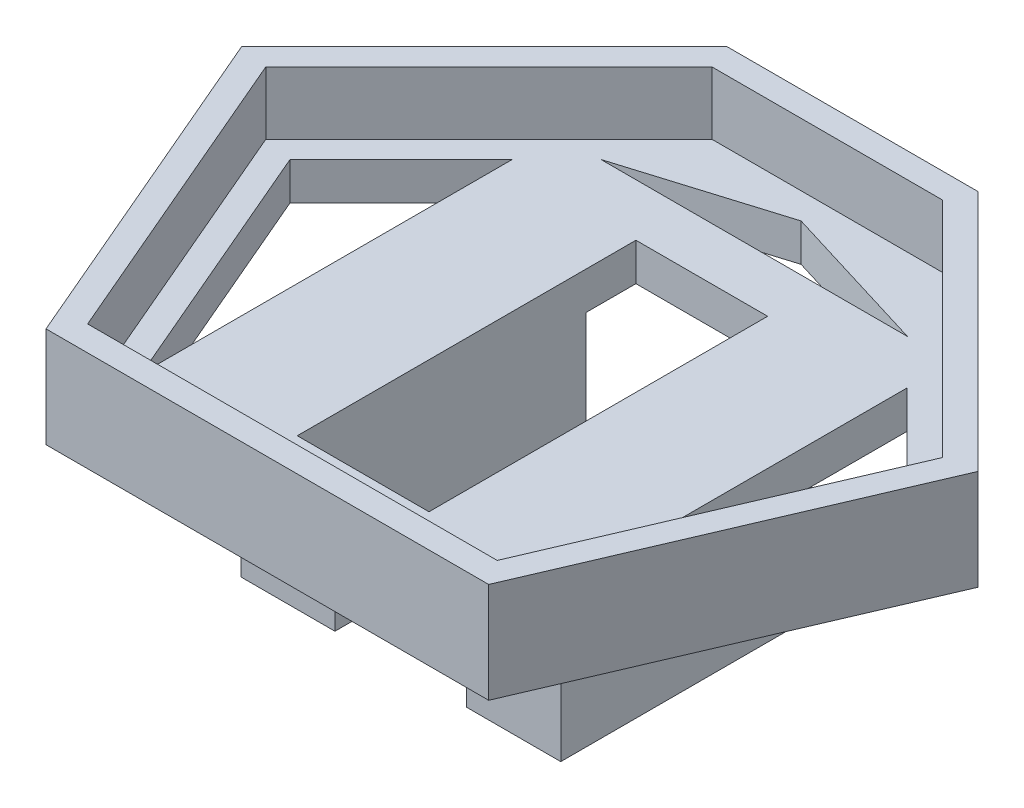
SolidWorks part; units mm, degrees
ref_plane "Front Plane" through (0, 0, 0) normal (0, 0, 1) x (1, 0, 0)
ref_plane "Top Plane" through (0, 0, 0) normal (0, 1, 0) x (1, 0, 0)
ref_plane "Right Plane" through (0, 0, 0) normal (1, 0, 0) x (0, 0, -1)
sketch "Sketch1" plane through (0, 0, 0) normal (0, 1, 0) x (1, 0, 0)
  line L2 (8.9892, 5.9961) -> (-8.9892, 5.9961) construction
  line L6 (-8.9892, 5.9961) -> (-26.3848, -11.3995) construction
  line L7 (-26.3848, -11.3995) -> (-16, -35.6421) construction
  line L8 (-16, -35.6421) -> (16, -35.6421) construction
  line L9 (16, -35.6421) -> (26.3848, -11.3995) construction
  line L11 (26.3848, -11.3995) -> (8.9892, 5.9961) construction
  line L12 (9.1963, 6.4961) -> (-9.1963, 6.4961)
  line L13 (-9.1963, 6.4961) -> (-26.9777, -11.2853)
  line L14 (-26.9777, -11.2853) -> (-16.3298, -36.1421)
  line L16 (-16.3298, -36.1421) -> (16.3298, -36.1421)
  line L17 (16.3298, -36.1421) -> (26.9777, -11.2853)
  line L18 (26.9777, -11.2853) -> (9.1963, 6.4961)
  line L19 (10.0247, 8.4961) -> (-10.0247, 8.4961)
  line L20 (-10.0247, 8.4961) -> (-29.3492, -10.8283)
  line L21 (-29.3492, -10.8283) -> (-17.6488, -38.1421)
  line L22 (-17.6488, -38.1421) -> (17.6488, -38.1421)
  line L23 (17.6488, -38.1421) -> (29.3492, -10.8283)
  line L24 (29.3492, -10.8283) -> (10.0247, 8.4961)
  dimension "D1" = 0.5
  dimension "D2" = 2
extrude "Boss-Extrude1" add sketch "Sketch1" along normal blind 5
sketch "Sketch2" plane through (0, 0, 0) normal (0, -1, 0) x (-1, 0, 0)
  line L0 (17.6488, -38.1421) -> (-17.6488, -38.1421)
  line L1 (-17.6488, -38.1421) -> (-29.3492, -10.8283)
  line L2 (-29.3492, -10.8283) -> (-10.0247, 8.4961)
  line L3 (-10.0247, 8.4961) -> (10.0247, 8.4961)
  line L4 (10.0247, 8.4961) -> (29.3492, -10.8283)
  line L5 (29.3492, -10.8283) -> (17.6488, -38.1421)
extrude "Boss-Extrude2" add sketch "Sketch2" along normal blind 3
sketch "Sketch3" plane through (0, -3, 0) normal (0, -1, 0) x (-1, 0, 0)
  line L0 (0, 8.4961) -> (0, -38.1421) construction
  line L1 (10.0247, 8.4961) -> (-10.0247, 8.4961) construction
  line L2 (-17.6488, -38.1421) -> (17.6488, -38.1421) construction
  line L3 (5.25, -7.5039) -> (12.7574, -7.5039)
  line L4 (5.25, -7.5039) -> (-5.25, -7.5039) construction
  line L5 (5.25, -7.5039) -> (5.25, -27.5039)
  line L6 (5.25, -27.5039) -> (-5.25, -27.5039) construction
  line L7 (-5.25, -7.5039) -> (-5.25, -27.5039)
  line L10 (12.7574, -7.5039) -> (12.7574, -27.5039)
  line L11 (12.7574, -27.5039) -> (5.25, -27.5039)
  line L12 (-12.7574, -27.5039) -> (-5.25, -27.5039)
  line L13 (-12.7574, -7.5039) -> (-12.7574, -27.5039)
  line L14 (-5.25, -7.5039) -> (-12.7574, -7.5039)
  dimension "D1" = 10.5
  dimension "D2" = 20
  dimension "D3" = 16
extrude "Boss-Extrude3" add sketch "Sketch3" along normal blind 12
sketch "Sketch5" plane through (0, 0, 7.5039) normal (0, 0, -1) x (-1, 0, 0)
  line L0 (0, -3) -> (0, -15.9929) construction
  line L1 (10.0247, -3) -> (-10.0247, -3) construction
  line L2 (-5.25, -15) -> (-5.25, -3) construction
  line L3 (-9.75, -13) -> (9.75, -13)
  line L4 (-9.75, -13) -> (-9.75, -10.85)
  line L5 (-9.75, -10.85) -> (9.75, -10.85)
  line L6 (9.75, -13) -> (9.75, -10.85)
  line L7 (-9.75, -13) -> (9.75, -10.85) construction
  line L8 (-9.75, -10.85) -> (9.75, -13) construction
  line L9 (-5.25, -15) -> (-12.7574, -15) construction
  point P5 (0, -11.925)
  dimension "D1" = 4.5
  dimension "D2" = 2
  dimension "D3" = 2.15
extrude "Cut-Extrude2" cut sketch "Sketch5" against normal blind 18
sketch "Sketch6" plane through (0, -3, 0) normal (0, -1, 0) x (-1, 0, 0)
  line L0 (0, 8.4961) -> (0, -38.1421) construction
  line L2 (5.25, -7.5039) -> (5.25, -30.5039)
  line L3 (5.25, -30.5039) -> (-5.25, -30.5039)
  line L4 (-5.25, -5.5039) -> (-5.25, -30.5039)
  line L5 (10.0247, 8.4961) -> (-10.0247, 8.4961) construction
  line L6 (-17.6488, -38.1421) -> (17.6488, -38.1421) construction
  line L7 (-10.0247, 8.4961) -> (-29.3492, -10.8283) construction
  line L8 (-29.3492, -10.8283) -> (-17.6488, -38.1421) construction
  line L11 (-24.6061, -11.7422) -> (-13.9719, -36.5671) construction
  line L12 (-24.6061, -11.7422) -> (-15.7574, -32.399)
  line L13 (-15.7574, -2.8934) -> (-15.7574, -32.399)
  line L14 (-12.7574, -7.5039) -> (-12.7574, -27.5039) construction
  line L15 (-12.2192, 0.677) -> (12.2192, 0.677)
  line L16 (-12.2192, 0.677) -> (0, 4.4128)
  line L17 (-15.7574, -2.8934) -> (-24.6061, -11.7422)
  line L18 (-7.1963, 5.6677) -> (-24.6061, -11.7422) construction
  line L19 (12.2192, 0.677) -> (0, 4.4128)
  line L20 (15.7574, -2.8934) -> (24.6061, -11.7422)
  line L21 (15.7574, -2.8934) -> (15.7574, -32.399)
  line L22 (24.6061, -11.7422) -> (15.7574, -32.399)
  line L23 (-5.25, -5.5039) -> (-5.25, -3.5039)
  line L24 (-5.25, -3.5039) -> (5.25, -3.5039)
  line L25 (5.25, -7.5039) -> (5.25, -3.5039)
  line L26 (-12.7574, -27.5039) -> (-5.25, -27.5039) construction
  point P31 (0, 0.677)
  dimension "D1" = 25
  dimension "D2" = 3
  dimension "D3" = 3
  dimension "D4" = 17
  dimension "D5" = 2
extrude "Cut-Extrude3" cut sketch "Sketch6" against normal through all
